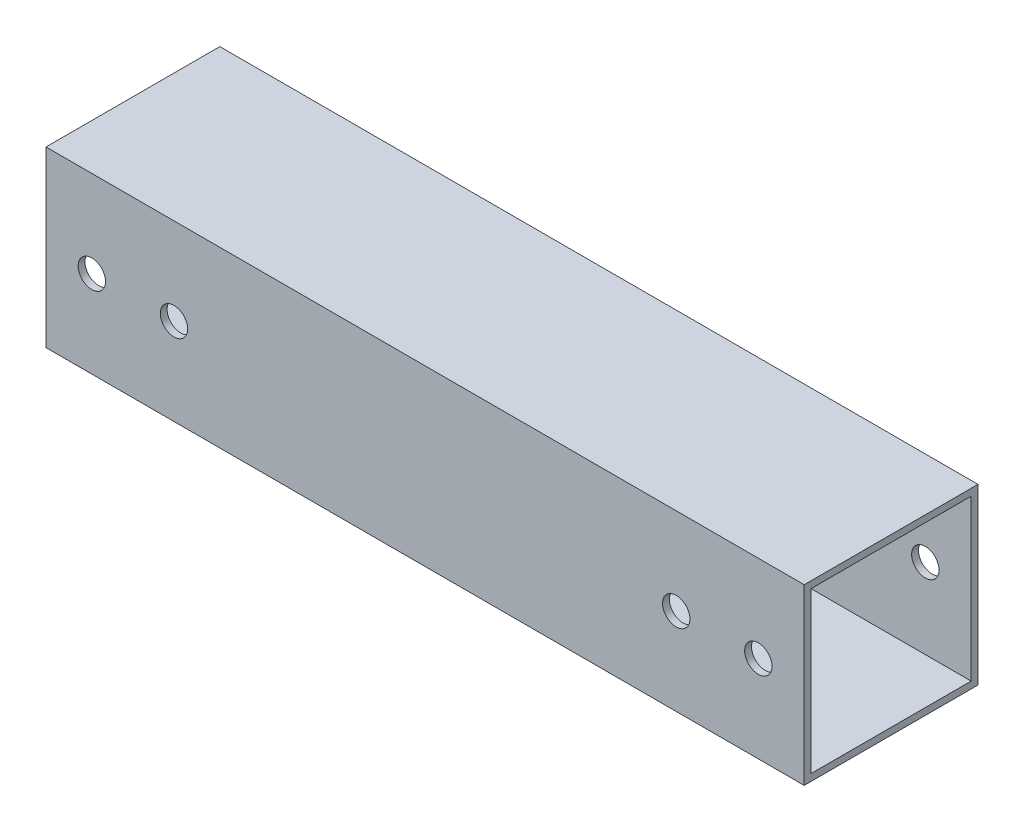
SolidWorks part; units mm, degrees
material "1060 Alloy"
ref_plane "Front Plane" through (0, 0, 0) normal (0, 0, 1) x (1, 0, 0)
ref_plane "Top Plane" through (0, 0, 0) normal (0, 1, 0) x (1, 0, 0)
ref_plane "Right Plane" through (0, 0, 0) normal (1, 0, 0) x (0, 0, -1)
sketch "Sketch1" plane through (0, 0, 0) normal (1, 0, 0) x (0, 0, -1)
  line L0 (-11.7, -11.7) -> (-11.7, 11.7)
  line L1 (12.7, -12.7) -> (-12.7, -12.7)
  line L2 (12.7, -12.7) -> (12.7, 12.7)
  line L3 (12.7, 12.7) -> (-12.7, 12.7)
  line L4 (-12.7, -12.7) -> (-12.7, 12.7)
  line L5 (12.7, -12.7) -> (-12.7, 12.7) construction
  line L6 (12.7, 12.7) -> (-12.7, -12.7) construction
  line L7 (11.7, 11.7) -> (-11.7, 11.7)
  line L8 (11.7, -11.7) -> (11.7, 11.7)
  line L9 (11.7, -11.7) -> (-11.7, -11.7)
  point P0 (0, 0)
  dimension "D1" = 1
extrude "Boss-Extrude1" add sketch "Sketch1" along normal blind 110.8
sketch "Sketch2" plane through (0, 0, 12.7) normal (0, 0, 1) x (1, 0, 0)
  circle A2 centre (92.1, 0) radius 2
  circle A3 centre (104.1, 0) radius 2
  circle A4 centre (6.7, 0) radius 2
  circle A5 centre (18.7, 0) radius 2
extrude "Cut-Extrude1" cut sketch "Sketch2" against normal through all both and the other way through all
